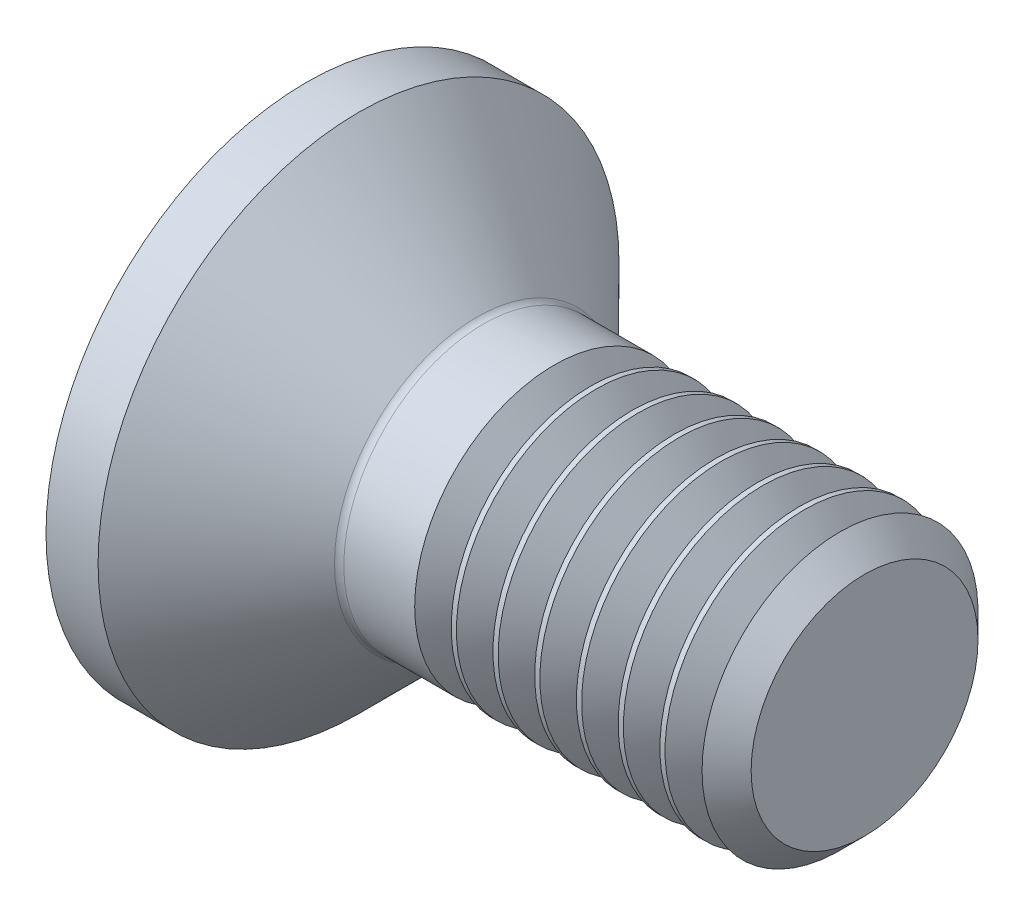
SolidWorks part; units mm, degrees
ref_plane "Plane1" through (0, 0, 0) normal (0, 0, 1) x (1, 0, 0)
ref_plane "Plane2" through (0, 0, 0) normal (0, 1, 0) x (1, 0, 0)
ref_plane "Plane3" through (0, 0, 0) normal (1, 0, 0) x (0, 0, -1)
sketch "BodySke" plane through (0, 0, 0) normal (0, 0, 1) x (1, 0, 0)
  line L0 (0, 0) -> (0, 2.8)
  line L1 (0.56, 2.8) -> (1.86, 1.5)
  line L2 (0, 2.8) -> (0.56, 2.8)
  line L3 (1.86, 1.5) -> (5.7195, 1.5)
  line L4 (6, 1.2195) -> (6, 0)
  line L5 (6, 0) -> (0, 0)
  line L6 (0, 0) -> (127, 0) construction
  line L7 (0.56, -2.8) -> (1.86, -1.5) construction
  line L8 (6, 1.2195) -> (5.7195, 1.5)
  line L9 (0, -2.8) -> (0.56, -2.8) construction
  line L10 (6, -1.2195) -> (5.7195, -1.5) construction
  line L11 (2.36, 7.85) -> (2.36, -14.375) construction
  line L12 (0, 19.05) -> (0, -3.175) construction
  dimension "D1" = 0.56
  dimension "Diameter" = 3
  dimension "Head_ht" = 1.86
  dimension "Length" = 6
  dimension "Body_ch_ang" = 45
  dimension "Head_dia" = 5.6
  dimension "Minor_dia" = 2.439
  dimension "Head_ang" = 90
  dimension "Advance" = 0.5
  dimension "Thread_nom" = 6
revolve "BaseBody" add sketch "BodySke" angle 360 about L6
cosmetic thread "ThreadCosmetic" [suppressed] parameters "Thread_length"=3.14, "Thread_minor"=2.439
fillet "Fillet1" radius 0.1 1 edges at (1.86, 0, 1.5)
sketch "Sketch2" plane through (0, 0, 0) normal (0, 0, 1) x (1, 0, 0)
  line L0 (0, 1) -> (1.1, 1)
  line L1 (1.1, 1) -> (1.6774, 0)
  line L2 (0, 0) -> (127, 0) construction
  line L3 (1.6774, 0) -> (0, 0)
  line L4 (0, 0) -> (0, 1)
  line L5 (0, -1) -> (1.1, -1) construction
  line L6 (0, 0) -> (47.625, 0) construction
  line L8 (0, 2.8) -> (0, -2.8) construction
  dimension "D2" = 60
  dimension "PreBroach_depth" = 1.1
  dimension "PreBroach_dia" = 2
revolve "PreBroach" cut sketch "Sketch2" angle 360 about L6
sketch "Sketch3" plane through (0, 0, 0) normal (-1, 0, 0) x (0, 0, 1)
  line L0 (-1, -0.5774) -> (-1, 0.5774)
  line L1 (-1, 0.5774) -> (0, 1.1547)
  line L2 (0, 1.1547) -> (1, 0.5774)
  line L3 (1, 0.5774) -> (1, -0.5774)
  line L4 (1, -0.5774) -> (0, -1.1547)
  line L5 (0, -1.1547) -> (-1, -0.5774)
  dimension "D1" = 1
  dimension "D2" = 1
  dimension "D3" = 2
  dimension "Hex_size" = 2
extrude "Hex" cut sketch "Sketch3" against normal blind 1.1
sketch "ThdSchSke" plane through (0, 0, 0) normal (0, 0, 1) x (1, 0, 0)
  line L0 (2.86, -1.2195) -> (2.6636, -1.5)
  line L1 (2.86, -1.2195) -> (3.0564, -1.5)
  line L2 (3.0564, -1.5) -> (3.0564, -1.875)
  line L3 (-3.175, 0) -> (5.1513, 0) construction
  line L4 (0, 2.8) -> (0, -2.8) construction
  line L5 (3.0564, -1.875) -> (2.6636, -1.875)
  line L6 (2.6636, -1.875) -> (2.6636, -1.5)
  dimension "Thread_minor" = 2.439
  dimension "Diameter" = 3
  dimension "Start" = 2.86
  dimension "SideAngle" = 55
  dimension "VeeAngle" = 70
  dimension "Overcut" = 3.75
revolve "ThreadSchematic" cut sketch "ThdSchSke" angle 360 about L3
pattern_linear "ThdSchPat" count 7 spacing 0.4486 along (1, 0, 0) of "ThreadSchematic"
equation "\"Thread_minor@ThreadCosmetic\"  =  \"Minor_dia@BodySke\""
equation "\"D1@Sketch3\" = \"Hex_size@Sketch3\" / 2"
equation "\"D2@Sketch3\" = \"D1@Sketch3\""
equation "\"D3@Sketch3\" = \"Hex_size@Sketch3\""
equation "\"Thread_length@ThreadCosmetic\" = ((sgn( (\"Length@BodySke\" - \"Advance@BodySke\" * 2.0 - \"Head_ht@BodySke\" ) - \"Thread_nom@BodySke\" )-1)*( (\"Length@BodySke\" - \"Advance@BodySke\" * 2.0 - \"Head_ht@BodySke\" ) - \"Thread_nom@BodySke\" ))/-2+ \"Thread_nom@BodySke\""
equation "\"Thread_minor@ThdSchSke\" = \"Minor_dia@BodySke\""
equation "\"Diameter@ThdSchSke\" = \"Diameter@BodySke\""
equation "\"Overcut@ThdSchSke\" = \"Diameter@BodySke\" * 1.25"
equation "\"Start@ThdSchSke\" = 0.000001 + \"Length@BodySke\" - \"Thread_length@ThreadCosmetic\"  '---Countersunk---"
equation "\"Num_threads@ThdSchPat\" = int( \"Thread_length@ThreadCosmetic\" / \"Advance@BodySke\" + 0.999 )  + 1"
equation "\"Advance@ThdSchPat\" = \"Thread_length@ThreadCosmetic\" /  (\"Num_threads@ThdSchPat\" - 1) 'relax it"
equation "\"Num_threads@ThdSchPat\" = \"Num_threads@ThdSchPat\" - sgn( \"Num_threads@ThdSchPat\" - 1) '---chamfered tips only---"
